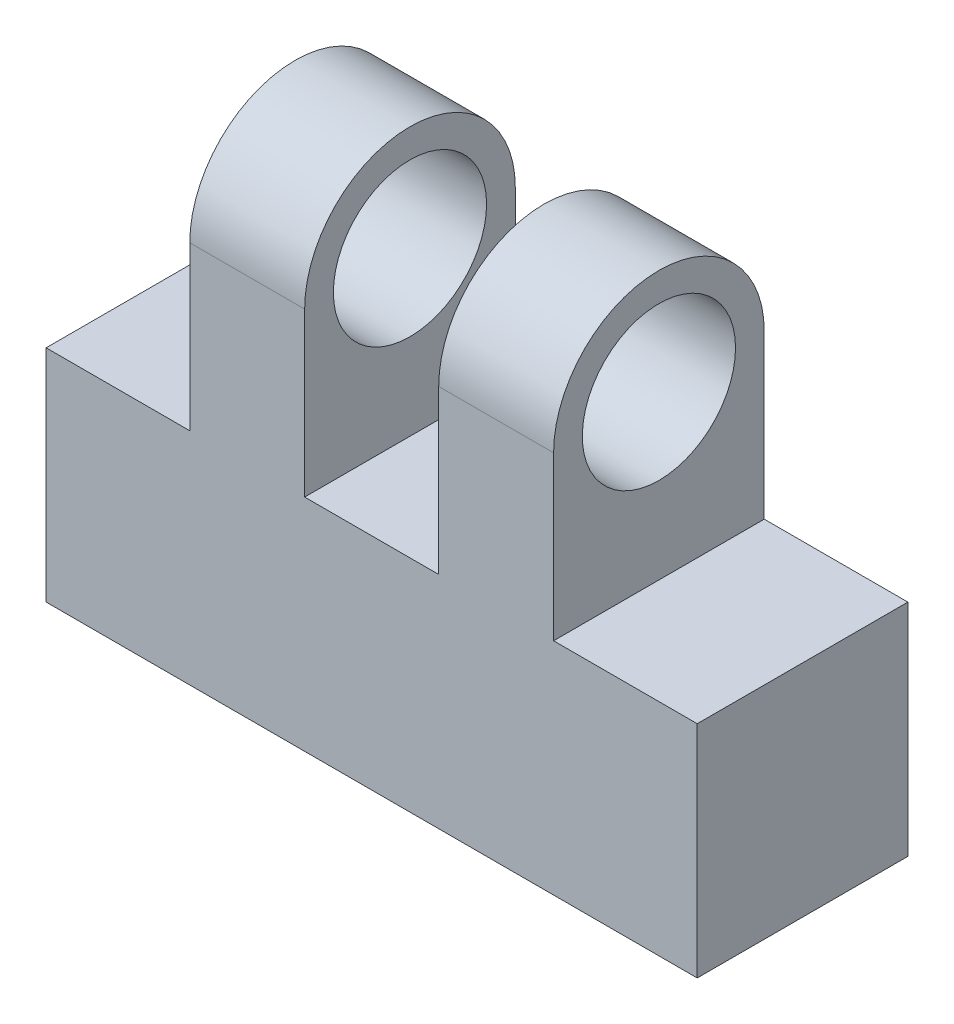
SolidWorks part; units mm, degrees
ref_plane "前视基准面" through (0, 0, 0) normal (0, 0, 1) x (1, 0, 0)
ref_plane "上视基准面" through (0, 0, 0) normal (0, 1, 0) x (1, 0, 0)
ref_plane "右视基准面" through (0, 0, 0) normal (1, 0, 0) x (0, 0, -1)
sketch "草图1" plane through (0, 0, 0) normal (1, 0, 0) x (0, 0, -1)
  line L1 (-5.5, 0) -> (-5.5, -20)
  line L2 (5.5, 0) -> (5.5, -20)
  line L3 (-5.5, -20) -> (5.5, -20)
  circle A0 centre (0, 0) radius 4
  arc A1 (5.5, 0) -> (-5.5, 0) centre (0, 0) ccw
  dimension "D1" = 8
  dimension "D2" = 11
  dimension "D3" = 20
extrude "凸台-拉伸1" add sketch "草图1" along normal blind 34
ref_plane "基准面1" through (0, 0, 5.5) normal (0, 0, 1) x (1, 0, 0)
sketch "草图2" plane through (0, 0, 5.5) normal (0, 0, 1) x (1, 0, 0)
  line L0 (17, 5.5) -> (17, -8.5) construction
  line L1 (20.5, 5.5) -> (13.5, 5.5)
  line L2 (34, 5.5) -> (0, 5.5) construction
  line L3 (13.5, 5.5) -> (13.5, -8.5)
  line L5 (7.5, -8.5) -> (7.5, 5.5)
  line L6 (7.5, 5.5) -> (0, 5.5)
  line L7 (0, 5.5) -> (0, -8.5)
  line L8 (0, 0) -> (0, -20) construction
  line L9 (0, -8.5) -> (7.5, -8.5)
  line L10 (13.5, -8.5) -> (20.5, -8.5)
  line L11 (17, -8.5) -> (17, 5.5)
  line L15 (20.5, 5.5) -> (20.5, -8.5)
  line L16 (34, -8.5) -> (26.5, -8.5)
  line L17 (34, 5.5) -> (34, -8.5)
  line L18 (26.5, 5.5) -> (34, 5.5)
  line L19 (26.5, -8.5) -> (26.5, 5.5)
  point P3 (17, 0)
  dimension "D1" = 3.5
  dimension "D2" = 14
  dimension "D3" = 6
extrude "切除-拉伸2" cut sketch "草图2" against normal through all contours L7 L9 L5 L6 | L15 L1 L11 L10 | L10 L11 L1 L3 | L19 L16 L17 L18
